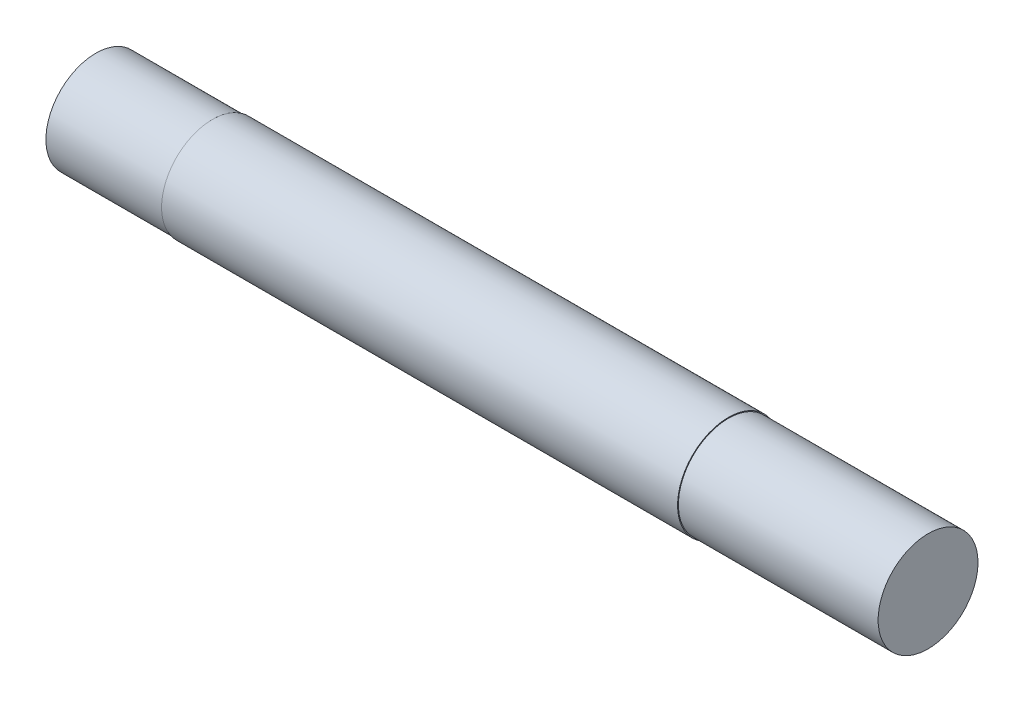
SolidWorks part; units mm, degrees
material "AISI 1020"
ref_plane "Front Plane" through (0, 0, 0) normal (0, 0, 1) x (1, 0, 0)
ref_plane "Top Plane" through (0, 0, 0) normal (0, 1, 0) x (1, 0, 0)
ref_plane "Right Plane" through (0, 0, 0) normal (1, 0, 0) x (0, 0, -1)
sketch "Sketch1" plane through (0, 0, 0) normal (0, 1, 0) x (1, 0, 0)
  line L0 (0, 0) -> (-9.079, 0) construction
  line L1 (0, 0) -> (7, 0)
  line L2 (0, 0) -> (0, 3)
  line L3 (0, 3) -> (7, 3)
  line L5 (7, 0) -> (38, 0)
  line L6 (7, 3) -> (7, 3.05)
  line L7 (7, 3.05) -> (38, 3.05)
  line L8 (38, 3) -> (38, 3.05)
  line L9 (38, 0) -> (50, 0)
  line L11 (38, 3) -> (50, 3)
  line L12 (50, 0) -> (50, 3)
  dimension "D1" = 6
  dimension "D2" = 7
  dimension "D3" = 6.1
  dimension "D4" = 31
  dimension "D5" = 12
  dimension "D6" = 50
revolve "Revolve1" add sketch "Sketch1" angle 360 about L0
cosmetic thread "Representação de rosca1" parameters "D2"=4.891
cosmetic thread "Representação de rosca2" parameters "D2"=4.891
